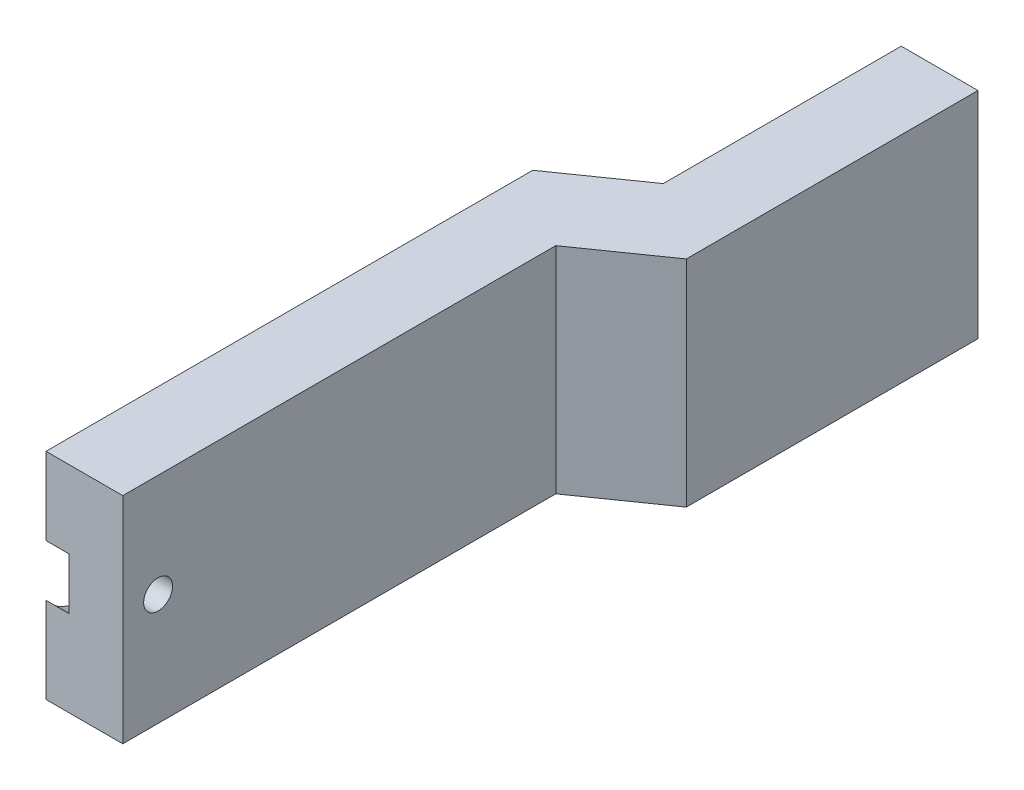
SolidWorks part; units mm, degrees
ref_plane "Front Plane" through (0, 0, 0) normal (0, 0, 1) x (1, 0, 0)
ref_plane "Top Plane" through (0, 0, 0) normal (0, 1, 0) x (1, 0, 0)
ref_plane "Right Plane" through (0, 0, 0) normal (1, 0, 0) x (0, 0, -1)
sketch "Croquis1" plane through (0, 0, 0) normal (0, 1, 0) x (1, 0, 0)
  line L0 (0, 0) -> (5, 0)
  line L1 (0, 0) -> (0, 31.7)
  line L2 (5, 0) -> (5, 28.2)
  line L5 (5, 35.2) -> (0, 31.7)
  line L8 (10, 31.7) -> (5, 28.2)
  line L9 (5, 35.2) -> (5, 50.7)
  line L10 (5, 50.7) -> (10, 50.7)
  line L11 (10, 50.7) -> (10, 31.7)
  dimension "D1" = 5
  dimension "D2" = 31.7
  dimension "D3" = 28.2
  dimension "D4" = 15.5
extrude "Saliente-Extruir1" add sketch "Croquis1" along normal blind 14
sketch "Croquis3" plane through (0, 0, 0) normal (0, -1, 0) x (1, 0, 0)
  line L0 (10, -50.7) -> (5, -50.7) construction
  circle A0 centre (2.5, -4.7) radius 1
  circle A1 centre (7.5, -46) radius 1
  dimension "D1" = 2
  dimension "D2" = 2
extrude "Cortar-Extruir1" cut sketch "Croquis3" against normal blind 5
sketch "Croquis5" plane through (0, 0, 0) normal (-1, 0, 0) x (0, 0, 1)
  circle A0 centre (-2.3, 7.28) radius 2.85
  dimension "D2" = 5.7
extrude "Cortar-Extruir2" cut sketch "Croquis5" against normal blind 1.5
sketch "Croquis6" plane through (1.5, 0, 0) normal (-1, 0, 0) x (0, 0, 1)
  circle A0 centre (-2.3, 7.28) radius 0.94
  dimension "D1" = 1.88
extrude "Cortar-Extruir3" cut sketch "Croquis6" against normal through all
